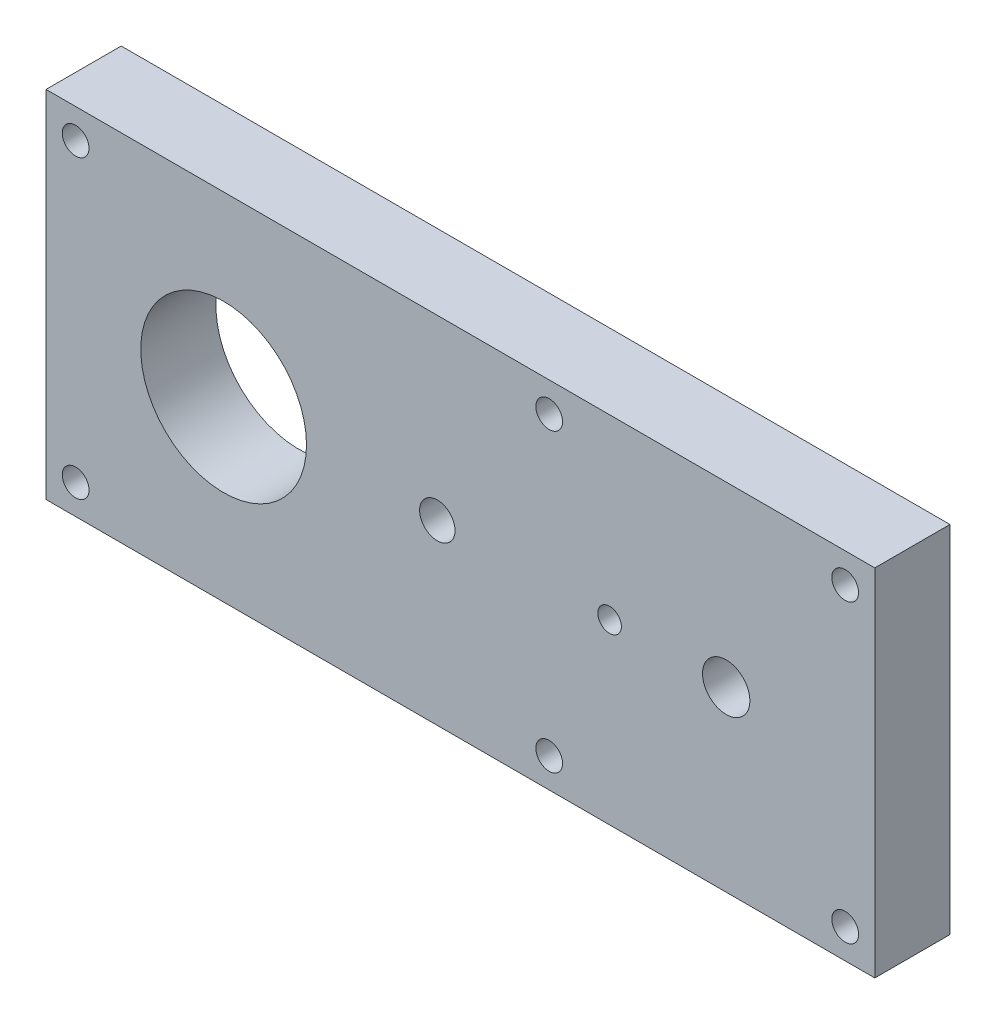
SolidWorks part; units mm, degrees
material "6061-T6 (SS)"
ref_plane "Front Plane" through (0, 0, 0) normal (0, 0, 1) x (1, 0, 0)
ref_plane "Top Plane" through (0, 0, 0) normal (0, 1, 0) x (1, 0, 0)
ref_plane "Right Plane" through (0, 0, 0) normal (1, 0, 0) x (0, 0, -1)
sketch "Sketch1" plane through (0, 0, 0) normal (0, 0, 1) x (1, 0, 0)
  line L0 (0, 0) -> (18.05, 0) construction
  line L1 (18.05, 0) -> (32.6, 0) construction
  line L2 (32.6, 0) -> (42.45, 0) construction
  line L3 (0, 0) -> (-15, 0) construction
  line L4 (-15, 15) -> (55, 15)
  line L5 (-15, 15) -> (-15, -15)
  line L6 (-15, -15) -> (55, -15)
  line L7 (55, 15) -> (55, -15)
  circle A0 centre (0, 0) radius 7
  circle A1 centre (18.05, 0) radius 1.495
  circle A2 centre (32.6, 0) radius 0.995
  circle A3 centre (42.45, 0) radius 2
  circle A4 centre (42.45, 0) radius 12 construction
  circle A5 centre (0, 0) radius 13.35 construction
  circle A6 centre (18.05, 0) radius 11.9 construction
  dimension "D1" = 14
  dimension "D2" = 2.99
  dimension "D4" = 1.99
  dimension "D6" = 4
  dimension "D10" = 24
  dimension "D12" = 26.7
  dimension "D13" = 23.8
  dimension "D3" = 18.05
  dimension "D5" = 14.55
  dimension "D7" = 9.85
  dimension "D8" = 30
  dimension "D9" = 15
  dimension "D11" = 70
extrude "Boss-Extrude1" add sketch "Sketch1" along normal blind 6.35
hole_wizard "#2 Clearance Hole1" positions "Sketch5" profile "Sketch4" hole size "#2" standard "ANSI Inch" end condition through all
sketch "Sketch5" plane through (0, 0, 6.35) normal (0, 0, 1) x (1, 0, 0)
  line L0 (-12.5, -12.5) -> (-12.5, 12.5) construction
  line L1 (-12.5, 12.5) -> (27.5, 12.5) construction
  line L5 (27.5, -12.5) -> (27.5, 12.5) construction
  line L7 (-12.5, -12.5) -> (27.5, -12.5) construction
  line L9 (-15, 15) -> (-15, -15) construction
  line L10 (55, 15) -> (-15, 15) construction
  line L11 (-15, -15) -> (55, -15) construction
  line L12 (27.5, -12.5) -> (52.5, -12.5) construction
  line L13 (52.5, -12.5) -> (52.5, 12.5) construction
  line L14 (52.5, 12.5) -> (27.5, 12.5) construction
  line L16 (55, -15) -> (55, 15) construction
  point P0 (-12.5, 12.5)
  point P2 (-12.5, -12.5)
  point P8 (27.5, 12.5)
  point P10 (27.5, -12.5)
  point P37 (52.5, 12.5)
  point P39 (52.5, -12.5)
  dimension "D1" = 2.5
  dimension "D2" = 2.5
  dimension "D3" = 2.5
  dimension "D4" = 2.5
  dimension "D5" = 40
sketch "Sketch4" plane through (-12.5, 12.5, 6.35) normal (1, 0, 0) x (0, -1, 0)
  line L0 (0, 0) -> (0, 6.35)
  line L1 (0, 6.35) -> (1.1303, 6.35)
  line L2 (1.1303, 6.35) -> (1.1303, 0)
  line L5 (1.1303, 0) -> (0, 0)
  line L11 (0, -6.35) -> (0, 107.95) construction
  dimension "Thru Hole Dia." = 2.2606
  dimension "Thru Hole Depth" = 6.35
sketch "Sketch6" plane through (0, 0, 6.35) normal (0, 0, 1) x (1, 0, 0)
  circle A0 centre (0, 0) radius 7
  dimension "D1" = 14
extrude "Cut-Extrude1" [suppressed] cut sketch "Sketch6" against normal blind 3.5
sketch "Sketch7" plane through (0, 0, 6.35) normal (0, 0, 1) x (1, 0, 0)
  circle A0 centre (18.05, 0) radius 3.5
  circle A1 centre (18.05, 0) radius 1.495 construction
  circle A2 centre (18.05, 0) radius 1.495
  dimension "D1" = 7
extrude "Boss-Extrude2" [suppressed] add sketch "Sketch7" along normal blind 2
sketch "Sketch8" plane through (0, 0, 6.35) normal (0, 0, 1) x (1, 0, 0)
  circle A0 centre (32.6, 0) radius 2
  circle A1 centre (32.6, 0) radius 0.995 construction
  circle A2 centre (32.6, 0) radius 0.995
  dimension "D1" = 4
extrude "Boss-Extrude3" [suppressed] add sketch "Sketch8" along normal blind 2
